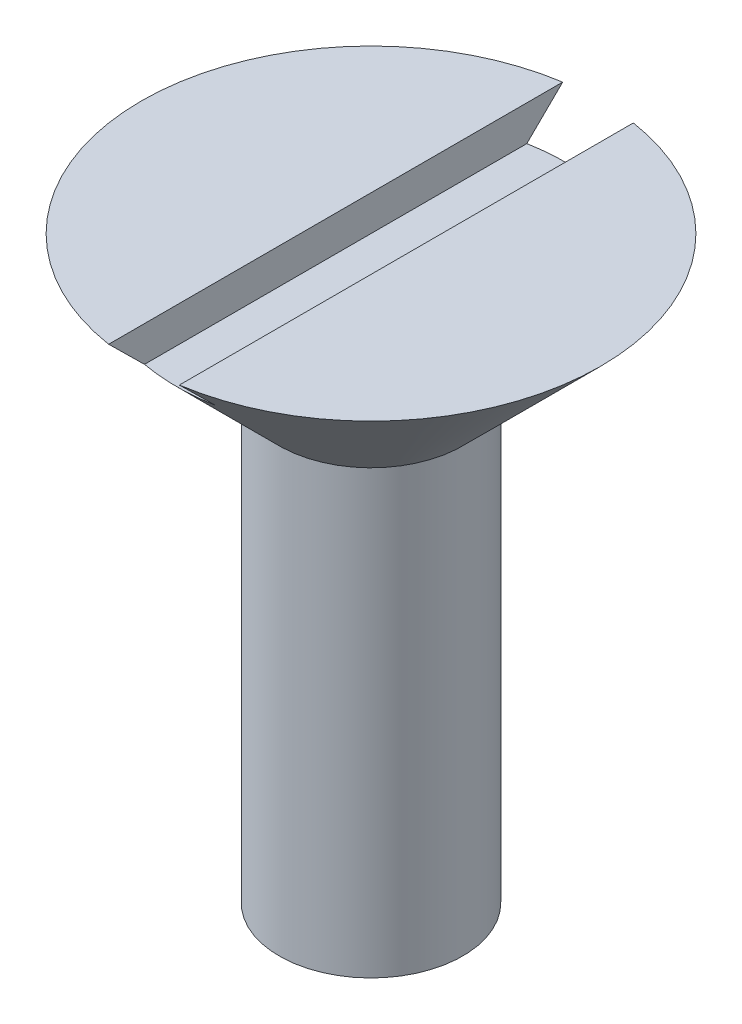
SolidWorks part; units mm, degrees
ref_plane "Front Plane" through (0, 0, 0) normal (0, 0, 1) x (1, 0, 0)
ref_plane "Top Plane" through (0, 0, 0) normal (0, 1, 0) x (1, 0, 0)
ref_plane "Right Plane" through (0, 0, 0) normal (1, 0, 0) x (0, 0, -1)
sketch "Sketch1" plane through (0, 0, 0) normal (0, 0, 1) x (1, 0, 0)
  line L0 (0, 49.5556) -> (0, -48.6406) construction
  line L1 (0, 49.5556) -> (6.5, 49.5556)
  line L2 (6.5, 49.5556) -> (2.5964, 45.6521)
  line L3 (2.5964, 45.6521) -> (2.5964, 33.1521)
  line L4 (2.5964, 33.1521) -> (0, 31.653)
  line L5 (0, 49.5556) -> (0, 31.653)
  dimension "D1" = 45
  dimension "D2" = 6.5
  dimension "D3" = 60
  dimension "D4" = 12.5
revolve "Revolve1" add sketch "Sketch1" angle 360 about L0
sketch "Sketch2" plane through (0, 0, 0) normal (0, 0, 1) x (1, 0, 0)
  line L0 (6.5, 49.5556) -> (-6.5, 49.5556) construction
  line L1 (-1, 50.5556) -> (1, 50.5556)
  line L2 (-1, 50.5556) -> (-1, 48.5556)
  line L3 (-1, 48.5556) -> (1, 48.5556)
  line L4 (1, 50.5556) -> (1, 48.5556)
  line L5 (-1, 50.5556) -> (1, 48.5556) construction
  line L6 (-1, 48.5556) -> (1, 50.5556) construction
  point P0 (0, 49.5556)
extrude "Cut-Extrude1" cut sketch "Sketch2" against normal mid plane 20
